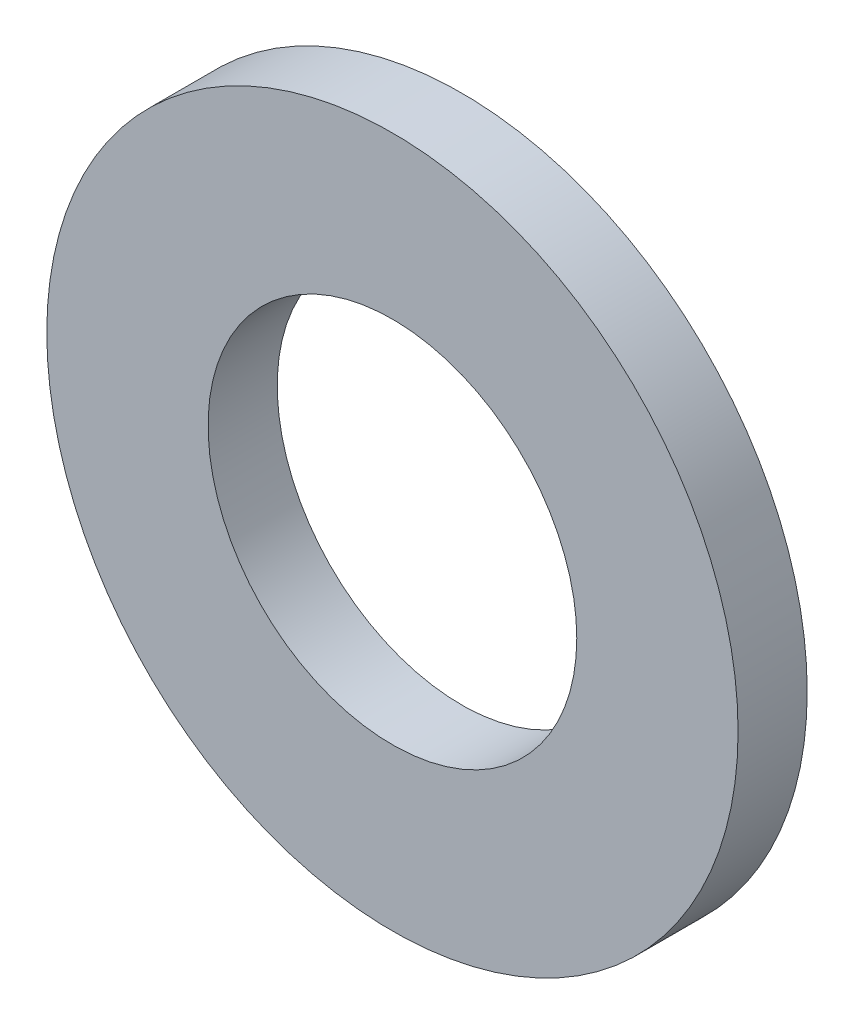
SolidWorks part; units mm, degrees
material "Thornel Mat VMA"
ref_plane "前视基准面" through (0, 0, 0) normal (0, 0, 1) x (1, 0, 0)
ref_plane "上视基准面" through (0, 0, 0) normal (0, 1, 0) x (1, 0, 0)
ref_plane "右视基准面" through (0, 0, 0) normal (1, 0, 0) x (0, 0, -1)
sketch "草图1" plane through (0, 0, 0) normal (0, 0, 1) x (1, 0, 0)
  circle A0 centre (0, 0) radius 8
  circle A1 centre (0, 0) radius 15
  dimension "D1" = 30
  dimension "D2" = 16
extrude "凸台-拉伸1" add sketch "草图1" along normal blind 3
